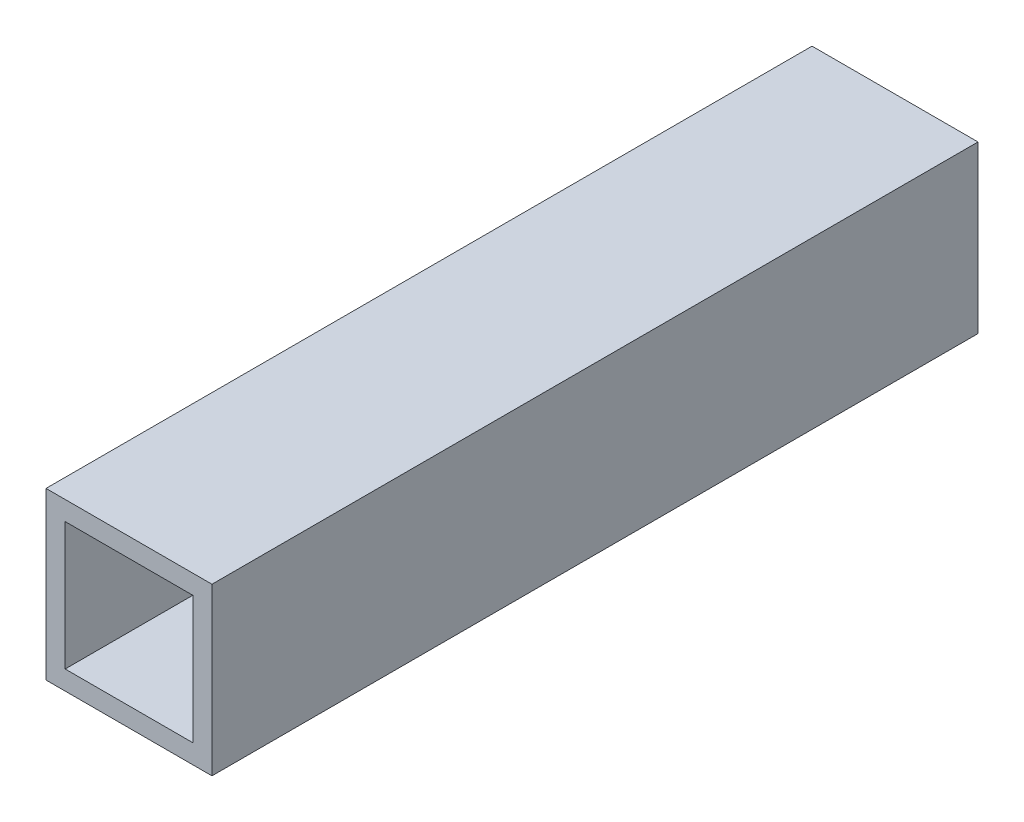
SolidWorks part; units mm, degrees
ref_plane "Front Plane" through (0, 0, 0) normal (0, 0, 1) x (1, 0, 0)
ref_plane "Top Plane" through (0, 0, 0) normal (0, 1, 0) x (1, 0, 0)
ref_plane "Right Plane" through (0, 0, 0) normal (1, 0, 0) x (0, 0, -1)
sketch "Sketch1" plane through (0, 0, 0) normal (0, 0, 1) x (1, 0, 0)
  line L1 (-6.5, 6.5) -> (6.5, 6.5)
  line L2 (-6.5, 6.5) -> (-6.5, -6.5)
  line L3 (-6.5, -6.5) -> (6.5, -6.5)
  line L4 (6.5, 6.5) -> (6.5, -6.5)
  line L5 (-6.5, 6.5) -> (6.5, -6.5) construction
  line L6 (-6.5, -6.5) -> (6.5, 6.5) construction
  line L7 (-5, -5) -> (5, -5)
  line L8 (-5, -5) -> (-5, 5)
  line L9 (-5, 5) -> (5, 5)
  line L10 (5, -5) -> (5, 5)
  line L11 (-5, -5) -> (5, 5) construction
  line L12 (-5, 5) -> (5, -5) construction
  point P0 (0, 0)
  point P6 (0, 0)
  dimension "D1" = 13
  dimension "D2" = 13
  dimension "D3" = 1.5
extrude "Boss-Extrude1" add sketch "Sketch1" along normal blind 60
